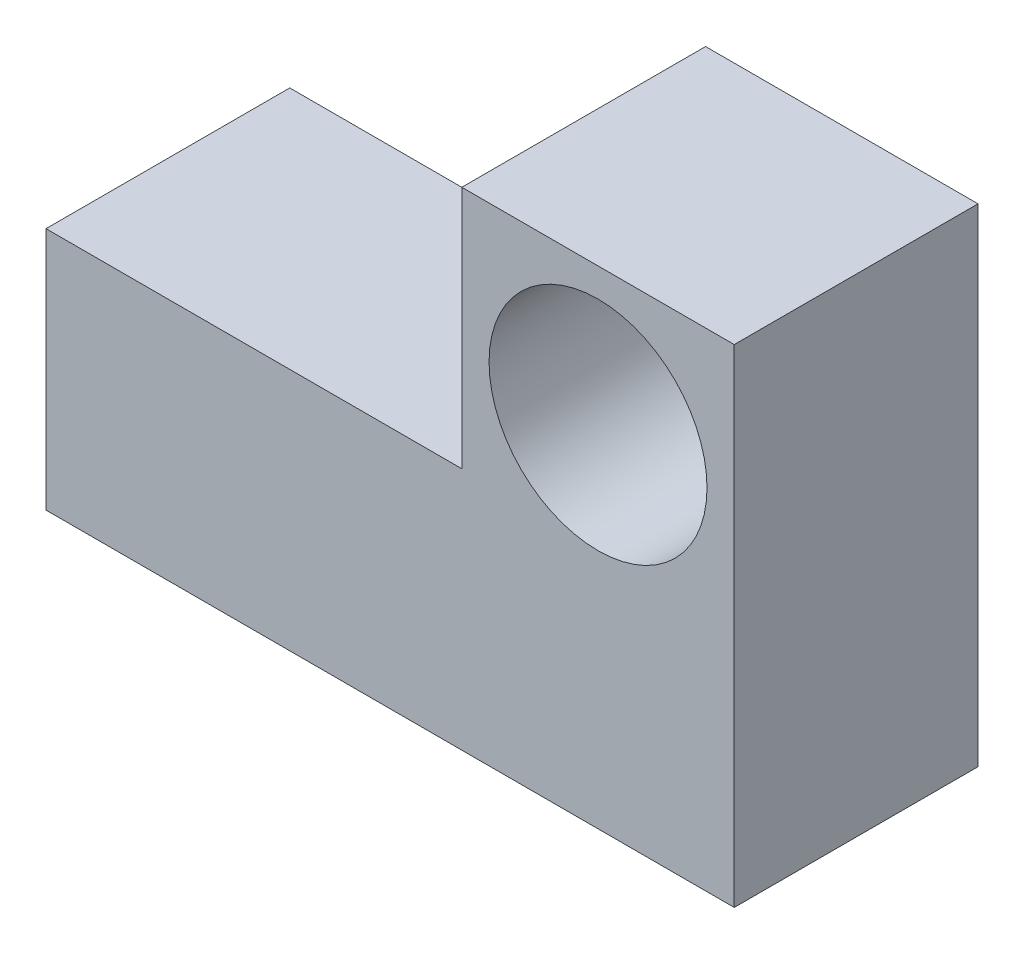
SolidWorks part; units mm, degrees
ref_plane "Front Plane" through (0, 0, 0) normal (0, 0, 1) x (1, 0, 0)
ref_plane "Top Plane" through (0, 0, 0) normal (0, 1, 0) x (1, 0, 0)
ref_plane "Right Plane" through (0, 0, 0) normal (1, 0, 0) x (0, 0, -1)
sketch "Sketch1" plane through (0, 0, 0) normal (0, 1, 0) x (1, 0, 0)
  line L1 (-15.24, -5.3975) -> (15.24, -5.3975)
  line L2 (-15.24, -5.3975) -> (-15.24, 5.3975)
  line L3 (-15.24, 5.3975) -> (15.24, 5.3975)
  line L4 (15.24, -5.3975) -> (15.24, 5.3975)
  line L5 (-15.24, -5.3975) -> (15.24, 5.3975) construction
  line L6 (-15.24, 5.3975) -> (15.24, -5.3975) construction
  point P0 (0, 0)
  dimension "D1" = 10.795
  dimension "D2" = 30.48
extrude "Boss-Extrude1" add sketch "Sketch1" along normal blind 10.795
sketch "Sketch2" plane through (-15.24, 0, 0) normal (-1, 0, 0) x (0, 0, 1)
  line L0 (-5.3975, 10.795) -> (-5.3975, 0) construction
  line L1 (-5.3975, 5.3975) -> (0, 5.3975) construction
  line L2 (0, 0) -> (0, 5.3975) construction
  circle A0 centre (0, 5.3975) radius 4.826
  dimension "D1" = 9.652
extrude "Cut-Extrude1" cut sketch "Sketch2" against normal blind 26.67
sketch "Sketch3" plane through (0, 10.795, 0) normal (0, 1, 0) x (1, 0, 0)
  line L1 (3.175, 5.3975) -> (15.24, 5.3975)
  line L2 (3.175, 5.3975) -> (3.175, -5.3975)
  line L3 (3.175, -5.3975) -> (15.24, -5.3975)
  line L4 (15.24, 5.3975) -> (15.24, -5.3975)
  line L5 (3.175, 5.3975) -> (15.24, -5.3975) construction
  line L6 (3.175, -5.3975) -> (15.24, 5.3975) construction
  line L8 (15.24, 5.3975) -> (-15.24, 5.3975) construction
  line L9 (-15.24, -5.3975) -> (15.24, -5.3975) construction
  line L10 (15.24, -5.3975) -> (15.24, 5.3975) construction
  point P0 (9.2075, 0)
  dimension "D1" = 12.065
extrude "Boss-Extrude2" add sketch "Sketch3" along normal blind 10.795
sketch "Sketch4" plane through (0, 0, -5.3975) normal (0, 0, -1) x (-1, 0, 0)
  line L0 (-9.2075, 21.59) -> (-9.2075, 0) construction
  line L1 (-15.24, 21.59) -> (-3.175, 21.59) construction
  line L3 (-15.24, 16.1925) -> (-3.175, 16.1925) construction
  line L5 (-3.175, 21.59) -> (-3.175, 10.795) construction
  line L6 (-15.24, 0) -> (15.24, 0) construction
  line L7 (-15.24, 21.59) -> (-15.24, 0) construction
  circle A0 centre (-9.2075, 15.494) radius 4.826
  point P11 (-9.2075, 20.32)
  dimension "D1" = 9.652
  dimension "D2" = 1.27
extrude "Cut-Extrude2" cut sketch "Sketch4" against normal blind 25.4
